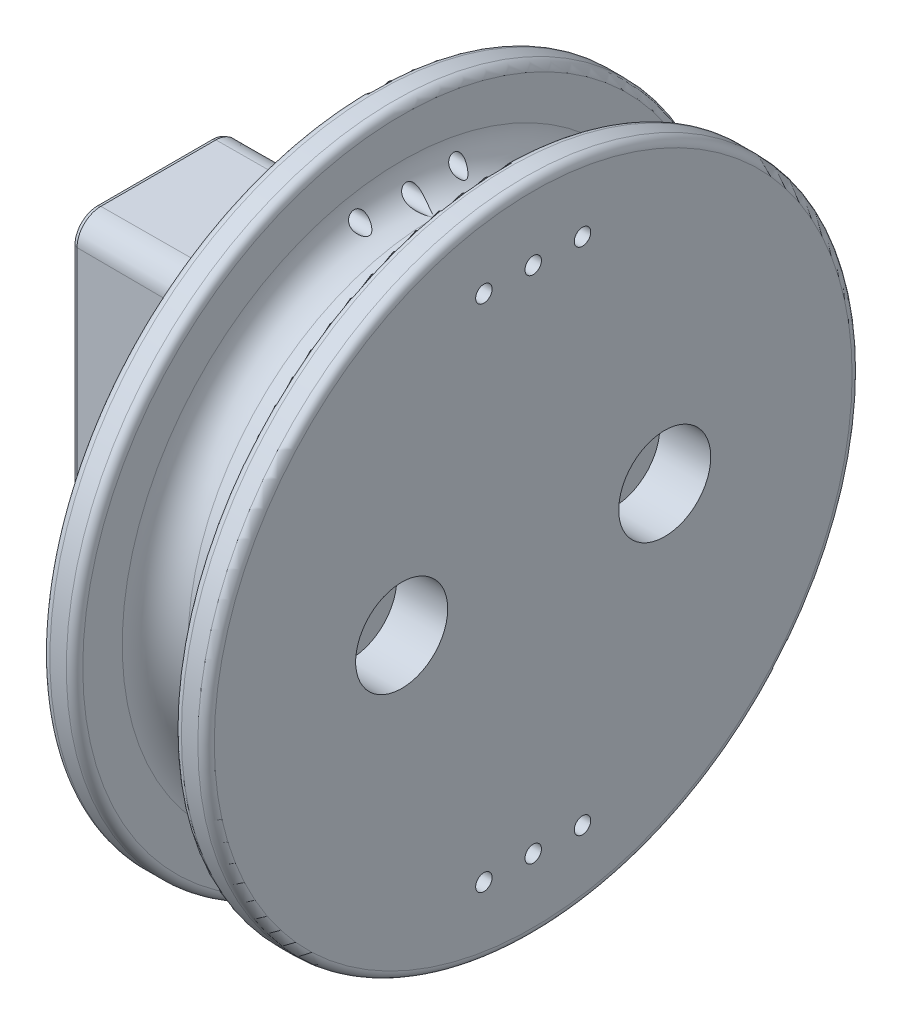
SolidWorks part; units mm, degrees
ref_plane "Ebene vorne" through (0, 0, 0) normal (0, 0, 1) x (1, 0, 0)
ref_plane "Ebene oben" through (0, 0, 0) normal (0, 1, 0) x (1, 0, 0)
ref_plane "Ebene rechts" through (0, 0, 0) normal (1, 0, 0) x (0, 0, -1)
ref_plane "Ebene1" through (3, 0, 0) normal (1, 0, 0) x (0, 0, -1)
sketch "Skizze1" plane through (0, 0, 0) normal (1, 0, 0) x (0, 0, -1)
  circle A0 centre (0, 0) radius 11.5
  dimension "D1" = 23
extrude "Aufsatz-Linear austragen1" add sketch "Skizze1" along normal blind 13
sketch "Skizze2" plane through (0, 0, 0) normal (1, 0, 0) x (0, 0, -1)
  line L0 (0, 17.4813) -> (0, -19.2829) construction
  line L1 (19.1866, 0) -> (-17.8656, 0) construction
  line L2 (5, -7.5) -> (5, 7.5)
  line L3 (3.5, 9) -> (-3.5, 9)
  line L4 (-5, -7.5) -> (-5, 7.5)
  line L5 (3.5, -9) -> (-3.5, -9)
  arc A0 (-5, -7.5) -> (-3.5, -9) centre (-3.5, -7.5) ccw
  arc A1 (3.5, -9) -> (5, -7.5) centre (3.5, -7.5) ccw
  arc A2 (-5, 7.5) -> (-3.5, 9) centre (-3.5, 7.5) cw
  arc A3 (5, 7.5) -> (3.5, 9) centre (3.5, 7.5) ccw
  point P9 (0, 9)
  point P10 (0, -9)
  point P12 (-5, 0)
  point P13 (5, 0)
  point P15 (-5, -9)
  point P18 (5, -9)
  point P21 (-5, 9)
  point P24 (5, 9)
  dimension "D3" = 1.5
  dimension "D1" = 18
  dimension "D2" = 10
extrude "Aufsatz-Linear austragen2" add sketch "Skizze2" against normal blind 10 draft 0.3
sketch "Skizze3" plane through (0, 0, 0) normal (1, 0, 0) x (0, 0, -1)
  line L0 (0, 16.115) -> (0, -14.9006) construction
  line L1 (15.3013, 0) -> (-17.9263, 0) construction
  line L2 (3, -6.5) -> (3, 6.5)
  line L3 (2, 7.5) -> (-2, 7.5)
  line L4 (-3, -6.5) -> (-3, 6.5)
  line L5 (2, -7.5) -> (-2, -7.5)
  arc A0 (3, -6.5) -> (2, -7.5) centre (2, -6.5) cw
  arc A1 (-2, -7.5) -> (-3, -6.5) centre (-2, -6.5) cw
  arc A2 (-3, 6.5) -> (-2, 7.5) centre (-2, 6.5) cw
  arc A3 (3, 6.5) -> (2, 7.5) centre (2, 6.5) ccw
  point P9 (0, 7.5)
  point P10 (0, -7.5)
  point P12 (-3, 0)
  point P13 (3, 0)
  point P15 (3, -7.5)
  point P18 (-3, -7.5)
  point P21 (-3, 7.5)
  point P24 (3, 7.5)
  dimension "D3" = 1
  dimension "D1" = 6
  dimension "D2" = 15
extrude "Schnitt-Linear austragen1" [suppressed] cut sketch "Skizze3" against normal through all and the other way through all
ref_axis "Achse1" through (11, 0, 0) along (-1, 0, 0)
hole_wizard "Stirnsenkung für M3 Zylinderschraube mit Innensechskant1" positions "Skizze5" profile "Skizze4" counterbore size "M3" standard "ANSI Metrisch" end condition through all
sketch "Skizze5" plane through (13, 0, 0) normal (1, 0, 0) x (0, 0, -1)
  line L0 (-20.2738, 0) -> (19.2387, 0) construction
  line L3 (0, 16.0743) -> (0, -16.0332) construction
  point P0 (8, 0)
  point P16 (-8, 0)
  dimension "D1" = 16
sketch "Skizze4" plane through (13, 0, -8) normal (0, 1, 0) x (0, 0, -1)
  line L0 (0, 0) -> (0, 23)
  line L1 (0, 23) -> (1.55, 23)
  line L3 (1.55, 23) -> (1.55, 3.1)
  line L4 (1.55, 3.1) -> (2.8, 3.1)
  line L5 (2.8, 3.1) -> (2.8, 0)
  line L7 (2.8, 0) -> (0, 0)
  line L11 (0, -6.35) -> (0, 107.95) construction
  dimension "Bohrerdurchmesser" = 3.1
  dimension "Bohrungstiefe" = 23
  dimension "Senkdurchmesser2" = 5.6
  dimension "Senktiefe2" = 3.1
sketch "Skizze7" plane through (13, 0, 0) normal (1, 0, 0) x (0, 0, -1)
  line L0 (0, 19.4022) -> (0, -18.8869) construction
  line L1 (-17.5053, 0) -> (18.7115, 0) construction
  line L2 (0, 0) -> (-14.4012, -10.0838) construction
  circle A0 centre (-7.3724, -5.1622) radius 1.25
  circle A1 centre (7.3724, -5.1622) radius 1.25
  circle A2 centre (7.3724, 5.1622) radius 1.25
  circle A3 centre (-7.3724, 5.1622) radius 1.25
  circle A4 centre (0, 0) radius 9 construction
  dimension "D1" = 2.5
  dimension "D3" = 35
  dimension "D2" = 18
extrude "Schnitt-Linear austragen2" [suppressed] cut sketch "Skizze7" against normal through all
sketch "Skizze6" plane through (3, 0, 0) normal (1, 0, 0) x (0, 0, -1)
  circle A0 centre (0, 0) radius 11.5
  circle A1 centre (0, 0) radius 19.9
  circle A2 centre (0, 0) radius 11.5 construction
  dimension "D1" = 39.8
extrude "Aufsatz-Linear austragen3" add sketch "Skizze6" along normal blind 10
fillet "Verrundung1" radius 1 8 edges at (0, -8.5607, 4.5607) (0, 0, 5) (0, 8.5607, 4.5607) (0, 9, 0) (0, 8.5607, -4.5607) (0, 0, -5) (0, -8.5607, -4.5607) (0, -9, 0)
chamfer "Fase1" [suppressed] distance 0.2 angle 45
chamfer "Fase2" distance 0.2 angle 20 8 edges at (-10, 0, 4.9476) (-10, -8.5236, 4.5236) (-10, 8.5236, 4.5236) (-10, -8.9476, 0) (-10, 8.9476, 0) (-10, -8.5236, -4.5236) (-10, 8.5236, -4.5236) (-10, 0, -4.9476)
sketch "Skizze8" plane through (0, 0, 0) normal (0, 1, 0) x (1, 0, 0)
  line L0 (8, -57.8615) -> (8, -40.4956) construction
  line L1 (3, 19.9) -> (3, -19.9) construction
  line L2 (13, -19.9) -> (13, 19.9) construction
  line L3 (11, -19.9) -> (11, -15)
  line L4 (3, -19.9) -> (13, -19.9) construction
  line L5 (11, -15) -> (5, -15)
  line L6 (5, -15) -> (5, -19.9)
  line L7 (5, -19.9) -> (11, -19.9)
  dimension "D1" = 6
  dimension "D2" = 15
revolve "Schnitt-Rotation1" cut sketch "Skizze8" angle 360 about axis through (11, 0, 0) along (-1, 0, 0)
fillet "Verrundung2" radius 2 2 edges at (11, 0, -15) (5, 0, -15)
fillet "Verrundung3" radius 0.5 4 edges at (3, 0, -19.9) (5, 0, -19.9) (13, 0, -19.9) (11, 0, -19.9)
fillet "Verrundung4" radius 2 1 edges at (3, 0, -11.5)
sketch "Skizze9" plane through (0, 0, 0) normal (1, 0, 0) x (0, 0, -1)
  line L0 (0, 0) -> (-20.5061, 20.5061) construction
  line L1 (0, 55.2166) -> (0, -54.4117) construction
  line L2 (-70.2668, 0) -> (56.8174, 0) construction
  circle A0 centre (-20.5061, 20.5061) radius 13.5
  circle A1 centre (-20.5061, -20.5061) radius 13.5
  circle A2 centre (20.5061, -20.5061) radius 13.5
  circle A3 centre (20.5061, 20.5061) radius 13.5
  dimension "D1" = 27
  dimension "D2" = 29
  dimension "D3" = 45
extrude "Schnitt-Linear austragen3" [suppressed] cut sketch "Skizze9" along normal through all
fillet "Verrundung5" [suppressed] radius 3
ref_plane "Ebene2" through (8, 0, 0) normal (1, 0, 0) x (0, 0, -1)
sketch "Skizze10" plane through (8, 0, 0) normal (1, 0, 0) x (0, 0, -1)
  line L0 (0, -35.627) -> (0, 32.7044) construction
  line L1 (32.735, 0) -> (-28.6232, 0) construction
  line L2 (9.4173, -15.5) -> (-7.2607, -15.5) construction
  circle A0 centre (3, -15.5) radius 0.5
  circle A1 centre (-3, -15.5) radius 0.5
  circle A2 centre (0, -15.5) radius 0.5
  dimension "D1" = 1
  dimension "D2" = 6
  dimension "D3" = 15.5
extrude "Schnitt-Linear austragen4" cut sketch "Skizze10" along normal through all and the other way blind 10
mirror "Spiegeln1" about plane through (0, 0, 0) normal (0, 1, 0) of "Schnitt-Linear austragen4"
